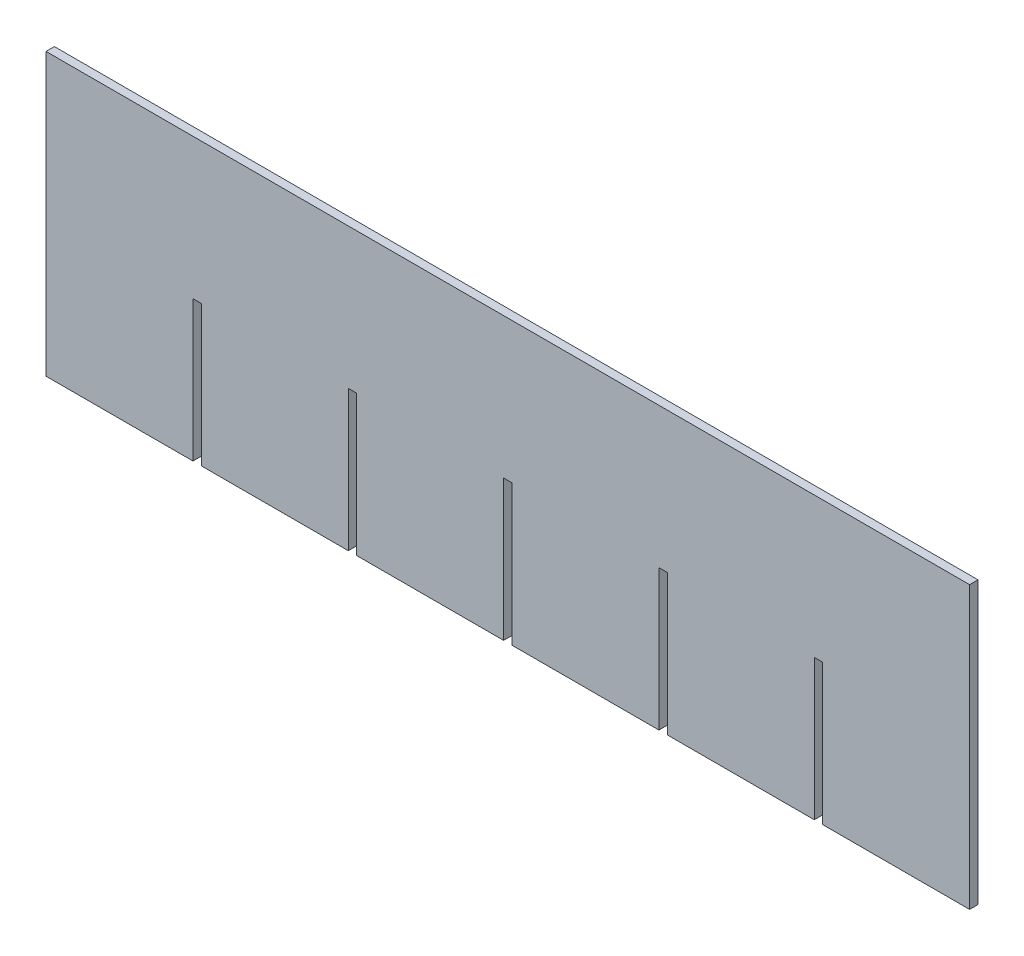
SolidWorks part; units mm, degrees
ref_plane "Front Plane" through (0, 0, 0) normal (0, 0, 1) x (1, 0, 0)
ref_plane "Top Plane" through (0, 0, 0) normal (0, 1, 0) x (1, 0, 0)
ref_plane "Right Plane" through (0, 0, 0) normal (1, 0, 0) x (0, 0, -1)
sketch "Sketch1" plane through (0, 0, 0) normal (0, 0, 1) x (1, 0, 0)
  line L1 (110, -33.5) -> (-110, -33.5)
  line L2 (110, -33.5) -> (110, 33.5)
  line L3 (110, 33.5) -> (-110, 33.5)
  line L4 (-110, -33.5) -> (-110, 33.5)
  line L5 (110, -33.5) -> (-110, 33.5) construction
  line L6 (110, 33.5) -> (-110, -33.5) construction
  point P0 (0, 0)
  dimension "D1" = 220
  dimension "D2" = 67
extrude "Boss-Extrude1" add sketch "Sketch1" along normal blind 2
sketch "Sketch2" plane through (0, 0, 2) normal (0, 0, 1) x (1, 0, 0)
  line L0 (-110, -33.5) -> (-75, -33.5)
  line L1 (-110, -33.5) -> (110, -33.5) construction
  line L2 (-75, -33.5) -> (-75, 0)
  line L3 (-75, 0) -> (-73, 0)
  line L4 (-73, 0) -> (-73, -33.5)
  line L5 (-55.5, 30.6513) -> (-55.5, -29.7508) construction
  line L6 (-75, -33.5) -> (-73, -33.5)
  line L7 (-36, 0) -> (-38, 0)
  line L8 (-36, -33.5) -> (-38, -33.5)
  line L9 (-36, -33.5) -> (-36, 0)
  line L10 (-38, 0) -> (-38, -33.5)
  line L11 (-18.5, 14.5003) -> (-18.5, -29.7508) construction
  line L12 (38, -33.5) -> (36, -33.5)
  line L13 (38, 0) -> (36, 0)
  line L14 (38, -33.5) -> (38, 0)
  line L15 (36, 0) -> (36, -33.5)
  line L16 (-1, -33.5) -> (1, -33.5)
  line L17 (-1, 0) -> (1, 0)
  line L18 (1, 0) -> (1, -33.5)
  line L19 (-1, -33.5) -> (-1, 0)
  line L20 (55.5, 14.5003) -> (55.5, -29.7508) construction
  line L21 (73, -33.5) -> (75, -33.5)
  line L22 (75, 0) -> (75, -33.5)
  line L23 (73, 0) -> (75, 0)
  line L24 (73, -33.5) -> (73, 0)
  point P27 (38, -16.75)
  line M22 (-110, -33.5) -> (110, -33.5)
  dimension "D1" = 35
  dimension "D2" = 2
  dimension "D3" = 17.5
  dimension "D4" = 17.5
  dimension "D5" = 17.5
extrude "Cut-Extrude1" cut sketch "Sketch2" against normal through all contours L7 L10 L9 M22 | L4 L3 L2 M22 | L24 L23 L22 L21 | L15 L12 L14 L13 | L19 L17 L18 L16
